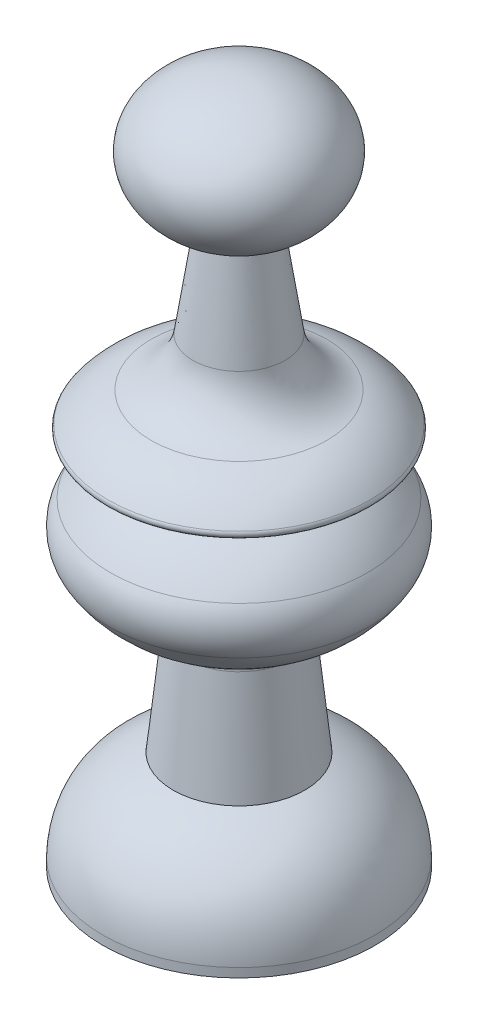
SolidWorks part; units mm, degrees
ref_plane "Front Plane" through (0, 0, 0) normal (0, 0, 1) x (1, 0, 0)
ref_plane "Top Plane" through (0, 0, 0) normal (0, 1, 0) x (1, 0, 0)
ref_plane "Right Plane" through (0, 0, 0) normal (1, 0, 0) x (0, 0, -1)
sketch "Sketch1" plane through (0, 0, 0) normal (0, 0, 1) x (1, 0, 0)
  line L0 (0, 0) -> (0, 57.15) construction
  line L1 (0, 0) -> (-11.5, 0)
  line L2 (-5.5562, 7.6173) -> (-4.6047, 16.755)
  line L3 (0, 30.1625) -> (-33.3364, 30.1625) construction
  line L4 (-11.5, 0) -> (-11.5, 57.15) construction
  line L5 (-4.4596, 30.086) -> (-4.4596, 30.988)
  line L6 (0, 57.15) -> (0, 0)
  line L7 (-4.4596, 30.988) -> (-11.5, 30.988)
  line L8 (0, 30.988) -> (-23.0188, 30.988) construction
  line L9 (-2.667, 46.3884) -> (-4.445, 34.5388)
  arc A0 (-10.8675, 26.1839) -> (-10.9384, 22.2413) centre (-7.944, 24.1594) ccw
  arc A3 (-4.6047, 16.755) -> (-5.7122, 18.3812) centre (-6.1205, 16.9129) ccw
  arc A4 (-10.9384, 22.2413) -> (-5.7122, 18.3812) centre (-3.2729, 27.1515) ccw
  arc A5 (-4.4596, 30.086) -> (-10.8675, 26.1839) centre (-3.2729, 20.9247) ccw
  ellipse E0 centre (0, 51.5874) end of major axis (7.5, 51.5874) minor radius 5.5626 (0, 57.15) -> (-2.667, 46.3884) ccw
  spline S0 degree 2 poles (-11.5, 0) (-11.2207, 5.5448) (-5.5562, 7.6173) knots 0 0 0 1 1 1
  spline S1 degree 2 poles (-11.5, 30.988) (-9.1982, 34.5483) (-4.445, 34.5388) knots 0 0 0 1 1 1
  point P16 (-4.7625, 15.24)
  dimension "D10" = 3.556
  dimension "D18" = 1.5768
  dimension "D1" = 57.15
  dimension "D2" = 23
  dimension "D3" = 9.525
  dimension "D4" = 11.1125
  dimension "D5" = 7.6173
  dimension "D6" = 3.5818
  dimension "D7" = 10.5804
  dimension "D8" = 15.24
  dimension "D9" = 30.1625
  dimension "D11" = 5.945
  dimension "D12" = 24.1594
  dimension "D13" = 20.9247
  dimension "D14" = 16.9129
  dimension "D15" = 6.1205
  dimension "D17" = 4.4596
  dimension "D19" = 1.3258
  dimension "D20" = 3.5508
  dimension "D16" = 30.988
  dimension "D21" = 4.445
  dimension "D22" = 15
  dimension "D23" = 11.1252
  dimension "D24" = 2.667
  dimension "D25" = 0.902
  dimension "D26" = 4.4596
revolve "Revolve2" add sketch "Sketch1" angle 360 about L6
sketch "Sketch2" plane through (0, 0, 0) normal (0, -1, 0) x (1, 0, 0)
  circle A1 centre (0, 0) radius 11.5
  circle A2 centre (0, 0) radius 11.5
  dimension "D1" = 0
extrude "Boss-Extrude1" add sketch "Sketch2" along normal blind 0.762 separate body
fillet "Fillet3" radius 0.381 3 edges at (0, 30.988, 11.5) (0, 30.988, 4.4596) (0, 30.086, 4.4596)
fillet "Fillet4" radius 5.08 1 edges at (0, 34.5388, 4.445)
